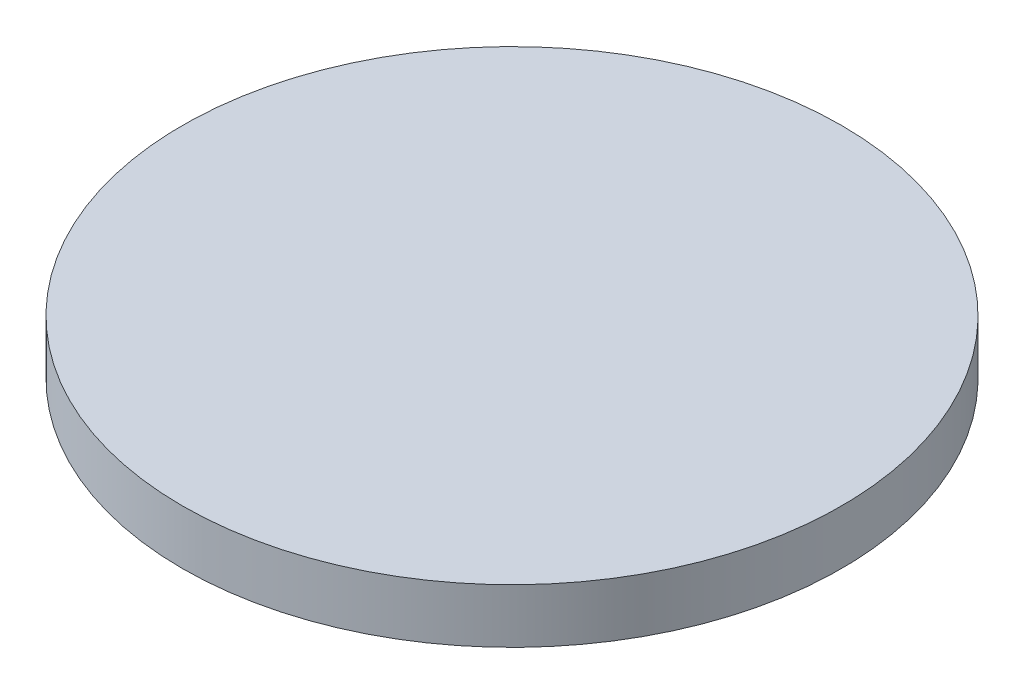
SolidWorks part; units mm, degrees
ref_plane "Front Plane" through (0, 0, 0) normal (0, 0, 1) x (1, 0, 0)
ref_plane "Top Plane" through (0, 0, 0) normal (0, 1, 0) x (1, 0, 0)
ref_plane "Right Plane" through (0, 0, 0) normal (1, 0, 0) x (0, 0, -1)
sketch "Sketch1" plane through (0, 0, 0) normal (0, 1, 0) x (1, 0, 0)
  circle A0 centre (0, 0) radius 8.5
  dimension "D1" = 17
extrude "Boss-Extrude1" add sketch "Sketch1" along normal blind 1.4
